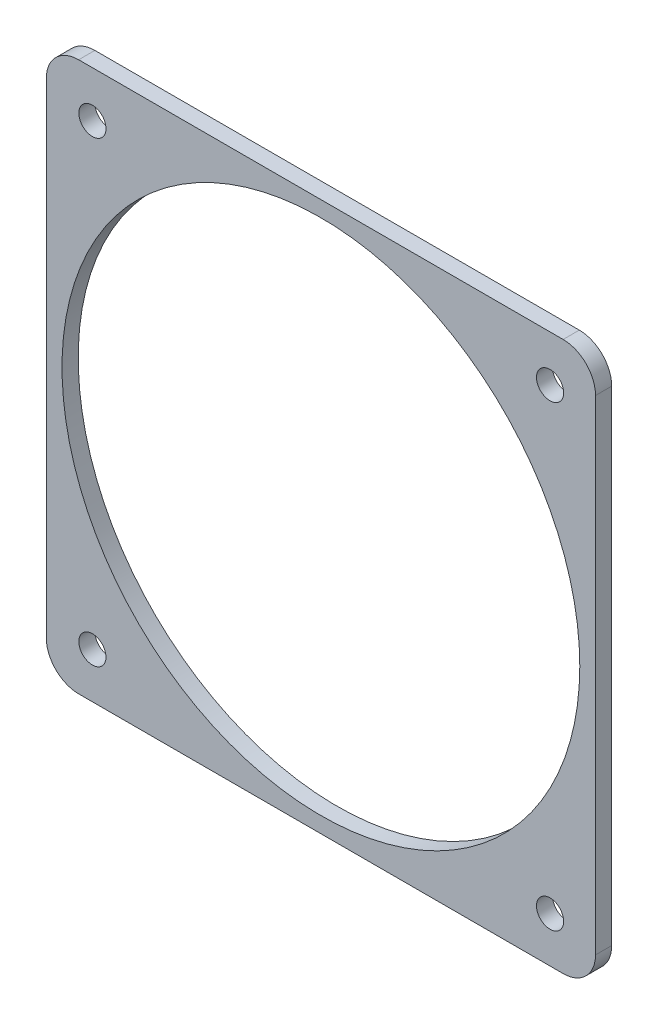
SolidWorks part; units mm, degrees
ref_plane "Front" through (0, 0, 0) normal (0, 0, 1) x (1, 0, 0)
ref_plane "Top" through (0, 0, 0) normal (0, 1, 0) x (1, 0, 0)
ref_plane "Right" through (0, 0, 0) normal (1, 0, 0) x (0, 0, -1)
sketch "Sketch1" plane through (0, 0, 0) normal (0, 0, 1) x (1, 0, 0)
  line L1 (-53.8815, -53.8815) -> (53.8815, -53.8815)
  line L2 (-53.8815, -53.8815) -> (-53.8815, 53.8815)
  line L3 (-53.8815, 53.8815) -> (53.8815, 53.8815)
  line L4 (53.8815, -53.8815) -> (53.8815, 53.8815)
  line L5 (-53.8815, -53.8815) -> (53.8815, 53.8815) construction
  line L6 (-53.8815, 53.8815) -> (53.8815, -53.8815) construction
  point P0 (0, 0)
  dimension "D1" = 152.4
extrude "Boss-Extrude1" add sketch "Sketch1" along normal blind 3.175 contours L2 L3 L4 L1
sketch "Sketch4" plane through (0, 0, 3.175) normal (0, 0, 1) x (1, 0, 0)
  line L0 (-53.8815, 0) -> (53.8815, 0) construction
  line L1 (-53.8815, -53.8815) -> (-53.8815, 53.8815) construction
  line L2 (53.8815, -53.8815) -> (53.8815, 53.8815) construction
  circle A0 centre (0, 0) radius 50.8
  dimension "D1" = 101.6
extrude "Cut-Extrude2" cut sketch "Sketch4" against normal up to next
fillet "Fillet1" radius 6.35 4 edges at (53.8815, 53.8815, 1.5875) (-53.8815, 53.8815, 1.5875) (-53.8815, -53.8815, 1.5875) (53.8815, -53.8815, 1.5875)
sketch "Sketch5" plane through (0, 0, 3.175) normal (0, 0, 1) x (1, 0, 0)
  circle A4 centre (-44.8387, 44.8387) radius 2.665
  circle A5 centre (44.9638, 44.8387) radius 2.665
  circle A6 centre (-44.8387, -44.9638) radius 2.665
  circle A7 centre (44.9638, -44.9638) radius 2.665
extrude "Cut-Extrude3" cut sketch "Sketch5" against normal up to next
